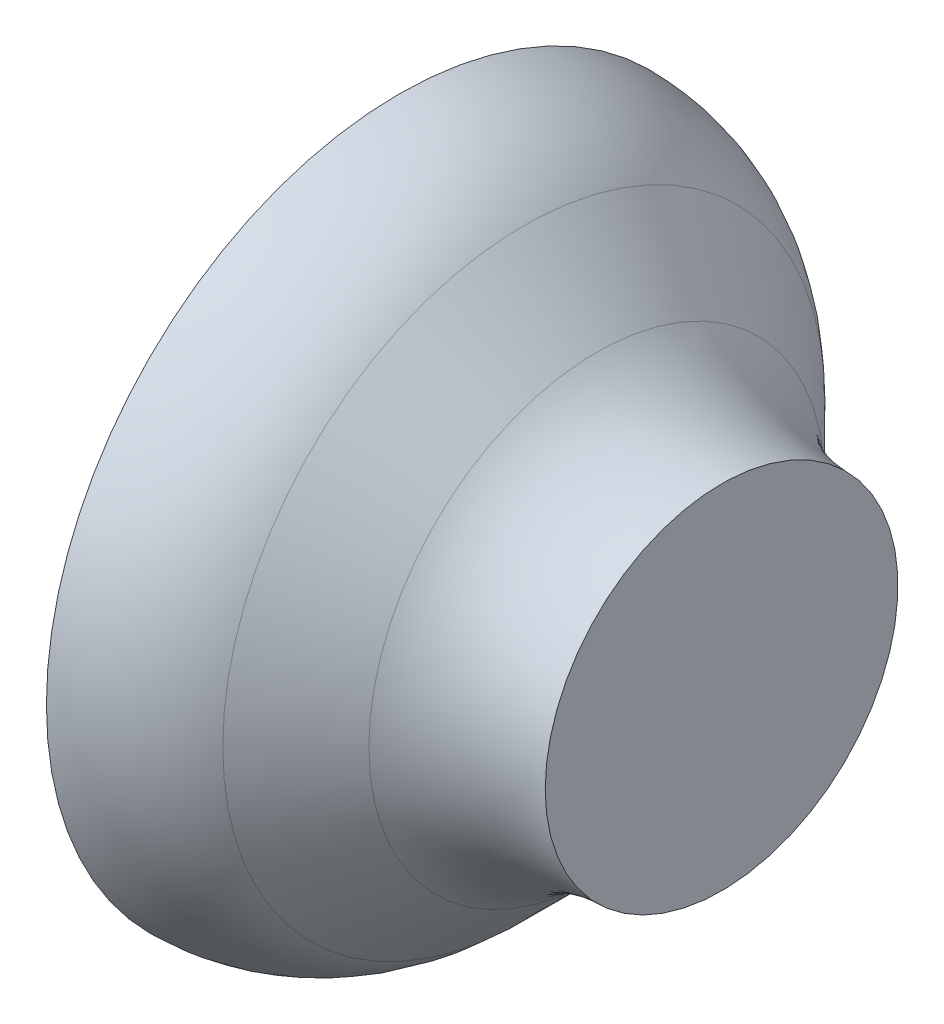
SolidWorks part; units mm, degrees
ref_plane "Front Plane" through (0, 0, 0) normal (0, 0, 1) x (1, 0, 0)
ref_plane "Top Plane" through (0, 0, 0) normal (0, 1, 0) x (1, 0, 0)
ref_plane "Right Plane" through (0, 0, 0) normal (1, 0, 0) x (0, 0, -1)
sketch "Sketch1" plane through (0, 0, 0) normal (0, 0, 1) x (1, 0, 0)
  line L0 (0, 0) -> (0, 35.7822) construction
  line L1 (0, 35.7822) -> (32.7126, 35.7822) construction
  line L2 (32.7126, 35.7822) -> (32.7126, 0) construction
  line L3 (32.7126, 0) -> (0, 0) construction
  line L4 (32.7126, 17.8911) -> (27.1428, 17.8911) construction
  line L5 (0, 35.7822) -> (0, 0)
  line L6 (12.6509, 30.542) -> (20.0617, 23.1313)
  line L7 (0, 0) -> (32.7126, 0)
  line L8 (32.7126, 0) -> (32.7126, 17.8911)
  arc A0 (32.7126, 17.8911) -> (20.0617, 23.1313) centre (32.7126, 35.7822) cw
  arc A1 (12.6509, 30.542) -> (0, 35.7822) centre (0, 17.8911) ccw
  point P12 (8.8061, 35.7822)
  dimension "D1" = 17.8911
  dimension "D3" = 35.7822
  dimension "D2" = 17.8911
  dimension "D4" = 45
revolve "Revolve1" add sketch "Sketch1" angle 360 about L7
equation "\"D1@Sketch1\"=\"D2@Sketch1\""
equation "\"D3@Sketch1\"=2.817496/2"
equation "\"D2@Sketch1\"=1.408748/2"
